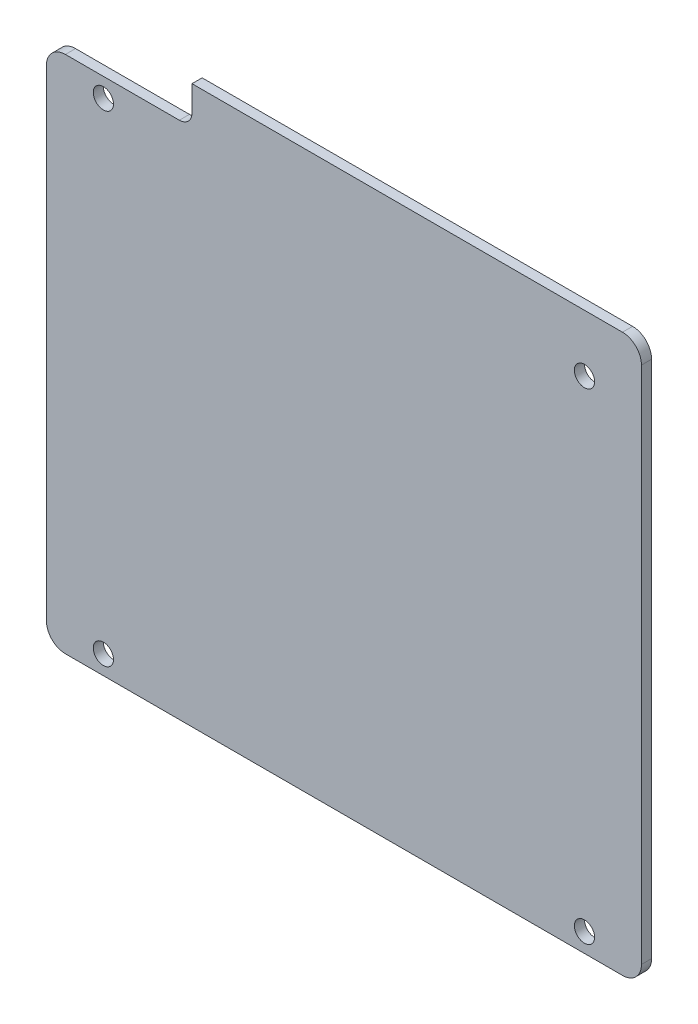
SolidWorks part; units mm, degrees
ref_plane "Front Plane" through (0, 0, 0) normal (0, 0, 1) x (1, 0, 0)
ref_plane "Top Plane" through (0, 0, 0) normal (0, 1, 0) x (1, 0, 0)
ref_plane "Right Plane" through (0, 0, 0) normal (1, 0, 0) x (0, 0, -1)
sketch "Sketch1" plane through (0, 0, 0) normal (0, 0, 1) x (1, 0, 0)
  line L1 (-87.5653, 82.9519) -> (-87.5653, 6.9519)
  line L2 (6.4347, 88.9519) -> (6.4347, 6.9519)
  line L3 (-64.5653, 91.9519) -> (0.9347, 91.9519)
  line L7 (-84.5653, 3.9519) -> (3.4347, 3.9519)
  line L8 (0.9347, 91.9519) -> (3.4347, 91.9519)
  line L19 (0.9347, 94.9519) -> (0.9347, 86.4519) construction
  line L20 (-64.5653, 91.9519) -> (-64.5653, 87.9519)
  line L22 (-66.5653, 85.9519) -> (-84.5653, 85.9519)
  arc A0 (3.4347, 3.9519) -> (6.4347, 6.9519) centre (3.4347, 6.9519) ccw
  arc A1 (-84.5653, 3.9519) -> (-87.5653, 6.9519) centre (-84.5653, 6.9519) cw
  arc A3 (3.4347, 91.9519) -> (6.4347, 88.9519) centre (3.4347, 88.9519) cw
  arc A4 (-64.5653, 87.9519) -> (-66.5653, 85.9519) centre (-66.5653, 87.9519) cw
  arc A5 (-84.5653, 85.9519) -> (-87.5653, 82.9519) centre (-84.5653, 82.9519) ccw
  dimension "D5" = 3
  dimension "D6" = 23
  dimension "D9" = 88
  dimension "D10" = 3
  dimension "D13" = 2
  dimension "D14" = 3
  dimension "D4" = 3
  dimension "D2" = 88
  dimension "D3" = 94
  dimension "D12" = 6
extrude "Boss-Extrude1" add sketch "Sketch1" along normal blind 1.6
hole_wizard "Ø3.2 (3.2) Diameter Hole3" positions "Sketch7" profile "Sketch6" hole size "Ø3.2" standard "Ansi Metric" end condition up to next
sketch "Sketch7" plane through (0, 0, 0) normal (0, 0, -1) x (-1, 0, 0)
  line L0 (87.5653, 82.9519) -> (87.5653, 6.9519) construction
  line L1 (-3.4347, 91.9519) -> (64.5653, 91.9519) construction
  line L2 (-6.4347, 6.9519) -> (-6.4347, 88.9519) construction
  line L3 (84.5653, 3.9519) -> (-3.4347, 3.9519) construction
  point P6 (78.5653, 6.9519)
  point P9 (78.5653, 82.9519)
  point P12 (2.5653, 82.9519)
  point P15 (2.5653, 6.9519)
  dimension "D1" = 9
  dimension "D2" = 9
  dimension "D3" = 9
  dimension "D4" = 9
  dimension "D5" = 9
  dimension "D6" = 3
  dimension "D7" = 3
  dimension "D8" = 9
sketch "Sketch6" plane through (-78.5653, 6.9519, 0) normal (1, 0, 0) x (0, 1, 0)
  line L0 (0, 0) -> (0, 1.6)
  line L1 (0, 1.6) -> (1.6, 1.6)
  line L2 (1.6, 1.6) -> (1.6, 0)
  line L5 (1.6, 0) -> (0, 0)
  line L11 (0, -6.35) -> (0, 107.95) construction
  dimension "Thru Hole Dia." = 3.2
  dimension "Thru Hole Depth" = 1.6
